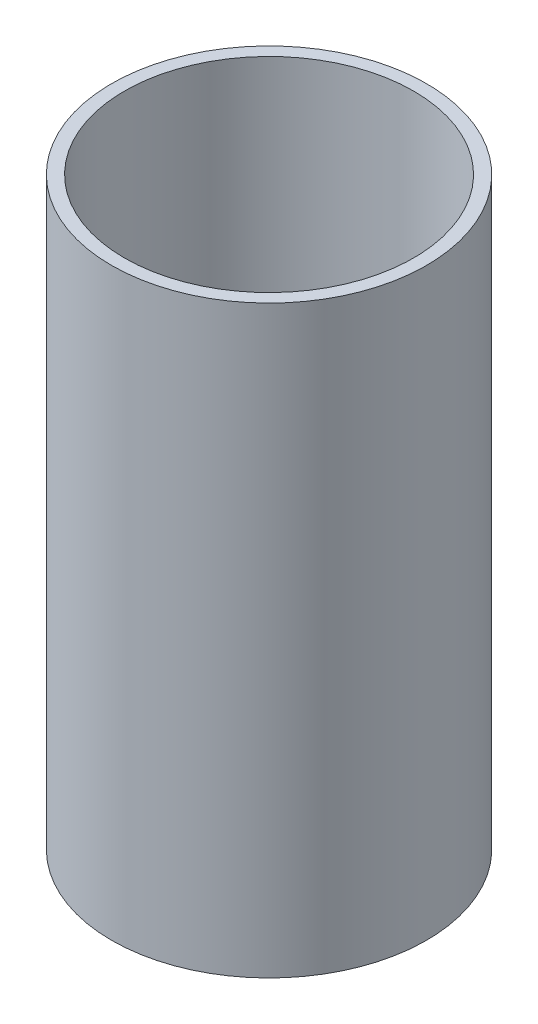
SolidWorks part; units mm, degrees
ref_plane "Front Plane" through (0, 0, 0) normal (0, 0, 1) x (1, 0, 0)
ref_plane "Top Plane" through (0, 0, 0) normal (0, 1, 0) x (1, 0, 0)
ref_plane "Right Plane" through (0, 0, 0) normal (1, 0, 0) x (0, 0, -1)
sketch "Sketch1" plane through (0, 0, 0) normal (0, 1, 0) x (1, 0, 0)
  circle A0 centre (0, 0) radius 13.208
  dimension "D1" = 26.416
extrude "Boss-Extrude1" add sketch "Sketch1" along normal blind 49.022
sketch "Sketch2" plane through (0, 49.022, 0) normal (0, 1, 0) x (1, 0, 0)
  circle A0 centre (0, 0) radius 12.1285
  dimension "D1" = 24.257
extrude "Cut-Extrude1" cut sketch "Sketch2" against normal offset from surface (47.117 mm away) 1.905 up to face at (0, 0, 13.208)
